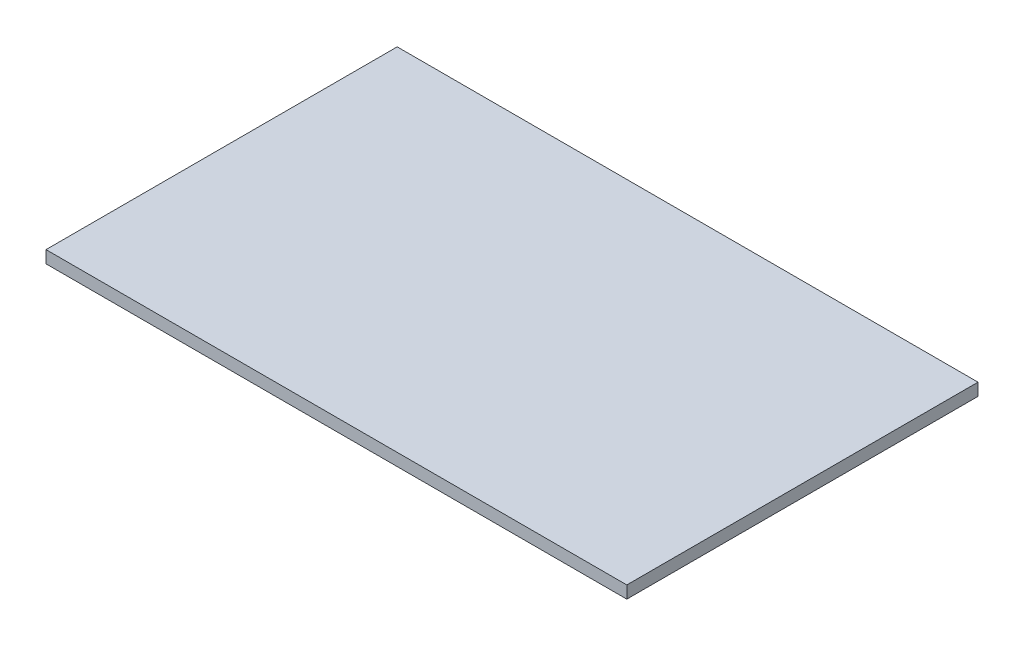
SolidWorks part; units mm, degrees
ref_plane "Front Plane" through (0, 0, 0) normal (0, 0, 1) x (1, 0, 0)
ref_plane "Top Plane" through (0, 0, 0) normal (0, 1, 0) x (1, 0, 0)
ref_plane "Right Plane" through (0, 0, 0) normal (1, 0, 0) x (0, 0, -1)
sketch "Sketch1" plane through (0, 0, 0) normal (0, 1, 0) x (1, 0, 0)
  line L1 (0, 0) -> (59.817, 0)
  line L2 (0, 0) -> (0, 36.1696)
  line L3 (0, 36.1696) -> (59.817, 36.1696)
  line L4 (59.817, 0) -> (59.817, 36.1696)
  dimension "D1" = 59.817
  dimension "D2" = 36.1696
extrude "Boss-Extrude1" add sketch "Sketch1" along normal blind 1.27
